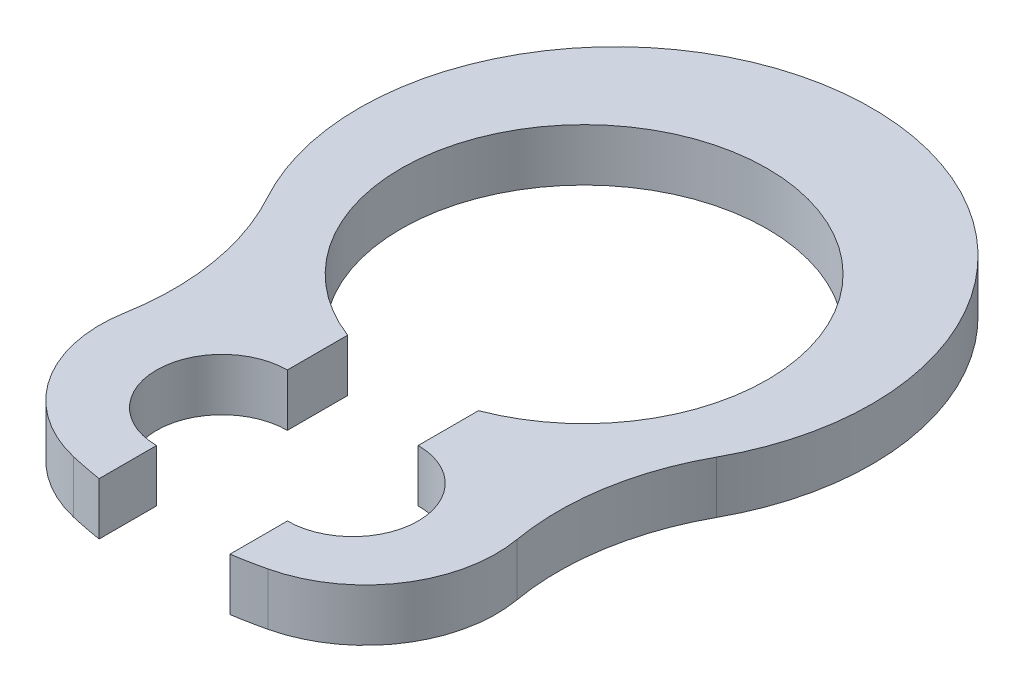
SolidWorks part; units mm, degrees
material "合金钢"
ref_plane "前视基准面" through (0, 0, 0) normal (0, 0, 1) x (1, 0, 0)
ref_plane "上视基准面" through (0, 0, 0) normal (0, 1, 0) x (1, 0, 0)
ref_plane "右视基准面" through (0, 0, 0) normal (1, 0, 0) x (0, 0, -1)
other "Configuration Table"
sketch "草图1" plane through (0, 0, 0) normal (0, 1, 0) x (1, 0, 0)
  line L0 (-0.5, -3.2077) -> (-0.5, -1.3077)
  line L1 (0.5, -1.3077) -> (0.5, -3.2077)
  line L2 (-0.5, -1.3077) -> (0.5, -1.3077) construction
  line L3 (-0.5, -2.2688) -> (0.5, -2.2688) construction
  arc A0 (-0.5, -1.3077) -> (0.5, -1.3077) centre (0, 0) cw
  arc A1 (-1.7174, -0.7045) -> (1.7174, -0.7045) centre (0, 0.24) cw
  arc A2 (0.5, -3.2077) -> (0.7443, -3.1599) centre (0, 0) ccw
  arc A4 (-0.5, -3.2077) -> (-0.7443, -3.1599) centre (0, 0) cw
  arc A6 (-1.7174, -0.7045) -> (-1.5, -2.0138) centre (-3.4699, -1.6682) cw
  arc A7 (-1.5, -2.0138) -> (-0.7443, -3.1599) centre (-0.515, -2.1866) ccw
  arc A8 (0.7443, -3.1599) -> (1.5, -2.0138) centre (0.515, -2.1866) ccw
  arc A9 (1.5, -2.0138) -> (1.7174, -0.7045) centre (3.4699, -1.6682) cw
  circle A10 centre (-0.5, -2.2688) radius 0.5 construction
  circle A11 centre (0.5, -2.2688) radius 0.5 construction
  circle A12 centre (0, 0) radius 2.3232 construction
  point P19 (0, 2.2)
  point P20 (0, 1.4)
  point P23 (0, -2.2688)
  dimension "d2" = 2.8
  dimension "d5" = 1
  dimension "d6" = 6.4928
  dimension "d7" = 4.6464
  dimension "r1" = 1
  dimension "r2" = 2
  dimension "dsp" = 0.24
  dimension "b" = 0.8
  dimension "t" = 1
  dimension "dh" = 1
  dimension "a" = 1.9
  dimension "D3" = 3
extrude "凸台-拉伸1" add sketch "草图1" along normal blind 0.4
sketch "草图2" plane through (0, 0.4, 0) normal (0, 1, 0) x (1, 0, 0)
  line L0 (-0.5, -2.2688) -> (0.5, -2.2688) construction
  line L1 (-0.5, -2.2688) -> (0.5, -2.2688) construction
  line L2 (-0.5, -3.2077) -> (-0.5, -1.3077)
  line L3 (0.5, -1.3077) -> (0.5, -3.2077)
  line L4 (-0.5, -3.2077) -> (-0.5, -1.3077)
  line L5 (0.5, -1.3077) -> (0.5, -3.2077)
  circle A0 centre (-0.5, -2.2688) radius 0.5 construction
  circle A1 centre (0.5, -2.2688) radius 0.5 construction
  circle A2 centre (-0.5, -2.2688) radius 0.5
  circle A3 centre (0.5, -2.2688) radius 0.5
  arc A8 (-0.7443, -3.1599) -> (-0.5, -3.2077) centre (0, 0) ccw
  arc A9 (0.5, -1.3077) -> (-0.5, -1.3077) centre (0, 0) ccw
  arc A10 (0.5, -3.2077) -> (0.7443, -3.1599) centre (0, 0) ccw
  arc A11 (0.7443, -3.1599) -> (1.5, -2.0138) centre (0.515, -2.1866) ccw
  arc A12 (1.7174, -0.7045) -> (1.5, -2.0138) centre (3.4699, -1.6682) ccw
  arc A13 (1.7174, -0.7045) -> (-1.7174, -0.7045) centre (0, 0.24) ccw
  arc A14 (-1.5, -2.0138) -> (-1.7174, -0.7045) centre (-3.4699, -1.6682) ccw
  arc A15 (-1.5, -2.0138) -> (-0.7443, -3.1599) centre (-0.515, -2.1866) ccw
  arc A16 (-0.7443, -3.1599) -> (-0.5, -3.2077) centre (0, 0) ccw
  arc A17 (0.5, -1.3077) -> (-0.5, -1.3077) centre (0, 0) ccw
  arc A18 (0.5, -3.2077) -> (0.7443, -3.1599) centre (0, 0) ccw
  arc A19 (0.7443, -3.1599) -> (1.5, -2.0138) centre (0.515, -2.1866) ccw
  arc A20 (1.7174, -0.7045) -> (1.5, -2.0138) centre (3.4699, -1.6682) ccw
  arc A21 (1.7174, -0.7045) -> (-1.7174, -0.7045) centre (0, 0.24) ccw
  arc A22 (-1.5, -2.0138) -> (-1.7174, -0.7045) centre (-3.4699, -1.6682) ccw
  arc A23 (-1.5, -2.0138) -> (-0.7443, -3.1599) centre (-0.515, -2.1866) ccw
  dimension "D1" = 0
extrude "切除-拉伸1" cut sketch "草图2" against normal through all contours A3 | A2
equation "\"dsp@草图1\"=0.3 * \"b@草图1\""
equation "\"d7@草图1\"= 0.5* (\"d2@草图1\" + \"d6@草图1\")"
equation "\"r1@草图1\" = \"d5@草图1\""
